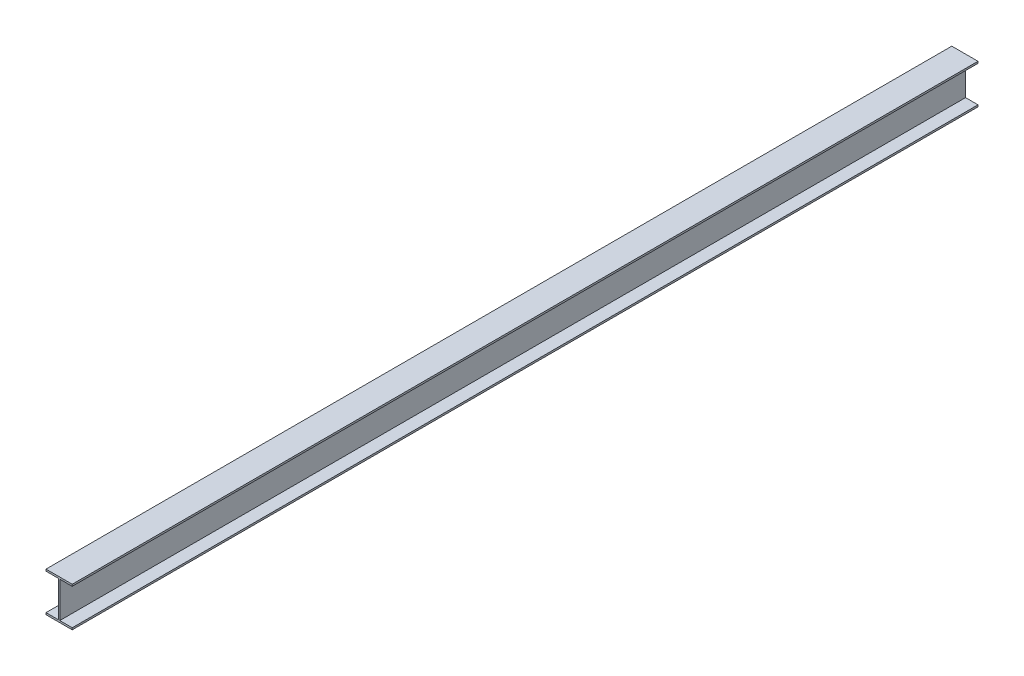
SolidWorks part; units mm, degrees
material "ASTM A992 Steel"
ref_plane "Front" through (0, 0, 0) normal (0, 0, 1) x (1, 0, 0)
ref_plane "Top" through (0, 0, 0) normal (0, 1, 0) x (1, 0, 0)
ref_plane "Right" through (0, 0, 0) normal (1, 0, 0) x (0, 0, -1)
sketch "Sketch1" plane through (0, 0, 0) normal (0, 0, 1) x (1, 0, 0)
  line L0 (0, -0.0002) -> (101.6, -0.0002)
  line L1 (101.6, -0.0002) -> (101.6, -7.1122)
  line L2 (101.6, -7.1122) -> (53.408, -7.1122)
  line L3 (53.408, -7.1122) -> (53.408, -146.0502)
  line L4 (53.408, -146.0502) -> (101.6, -146.0502)
  line L5 (101.6, -146.0502) -> (101.6, -153.1622)
  line L6 (101.6, -153.1622) -> (0, -153.1622)
  line L7 (0, -153.1622) -> (0, -146.0502)
  line L8 (0, -146.0502) -> (47.566, -146.0502)
  line L9 (47.566, -146.0502) -> (47.566, -7.1122)
  line L10 (47.566, -7.1122) -> (0, -7.1122)
  line L11 (0, -7.1122) -> (0, -0.0002)
  line L12 (50.8, -0.0002) -> (50.8, -153.1622) construction
  dimension "D1" = 5.842
  dimension "D2" = 7.112
  dimension "D3" = 7.112
  dimension "D4" = 7.112
  dimension "D5" = 153.162
  dimension "D6" = 50.8
  dimension "D7" = 50.8
  dimension "D8" = 47.566
extrude "Boss-Extrude1" add sketch "Sketch1" along normal blind 3510
